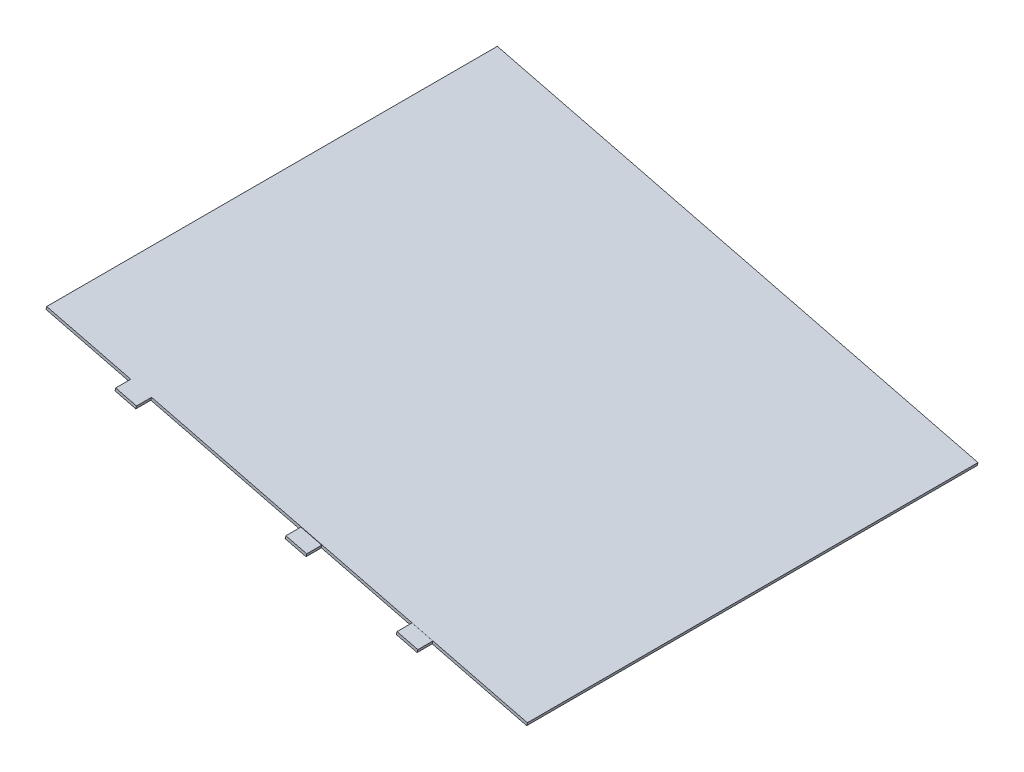
SolidWorks part; units mm, degrees
ref_plane "前视基准面" through (0, 0, 0) normal (0, 0, 1) x (1, 0, 0)
ref_plane "上视基准面" through (0, 0, 0) normal (0, 1, 0) x (1, 0, 0)
ref_plane "右视基准面" through (0, 0, 0) normal (1, 0, 0) x (0, 0, -1)
sketch "草图2" plane through (0, 0, 0) normal (0, 0, 1) x (1, 0, 0)
  line L0 (-2057.9413, 0) -> (-457.9413, 0) construction
  line L1 (-2057.9413, 0) -> (-2057.9413, 400) construction
  line L2 (-2057.9413, 400) -> (-457.9413, 0)
  line L3 (-457.9413, 0) -> (-2057.9413, 400)
  line L4 (-457.9413, 0) -> (-461.1955, -13.0171)
  line L5 (-461.1955, -13.0171) -> (-2061.1955, 386.9829)
  line L6 (-2061.1955, 386.9829) -> (-2057.9413, 400)
extrude "拉伸-薄壁1" add sketch "草图2" along normal blind 1500 thin contours L2
sketch "草图3" plane through (0, 0, 1500) normal (0, 0, 1) x (1, 0, 0)
  line L0 (-1778.2965, 330.0888) -> (-1780.7219, 320.3874)
  line L1 (-1778.2965, 330.0888) -> (-1708.884, 312.7357)
  line L2 (-1780.7219, 320.3874) -> (-1711.3093, 303.0343)
  line L3 (-1708.884, 312.7357) -> (-1711.3093, 303.0343)
  line L4 (-2057.9413, 400) -> (-457.9413, 0) construction
  line L5 (-2060.3666, 390.2986) -> (-460.3666, -9.7014) construction
extrude "凸台-拉伸2" add sketch "草图3" along normal blind 50 contours L0 L1 L3 L2
sketch "草图8" plane through (0, 0, 1500) normal (0, 0, 1) x (1, 0, 0)
  line L0 (-841.9625, 95.7704) -> (-844.3879, 86.0689)
  line L1 (-841.9625, 95.7704) -> (-772.55, 78.4172)
  line L2 (-844.3879, 86.0689) -> (-774.9753, 68.7158)
  line L3 (-772.55, 78.4172) -> (-774.9753, 68.7158)
extrude "凸台-拉伸5" add sketch "草图8" along normal blind 50
sketch "草图9" plane through (0, 0, 1500) normal (0, 0, 1) x (1, 0, 0)
  line L0 (-1211.8308, 187.1371) -> (-1214.2561, 177.4357)
  line L1 (-1211.8308, 187.1371) -> (-1142.4182, 169.784)
  line L2 (-1214.2561, 177.4357) -> (-1144.8436, 160.0826)
  line L3 (-1142.4182, 169.784) -> (-1144.8436, 160.0826)
extrude "凸台-拉伸6" add sketch "草图9" along normal blind 50
